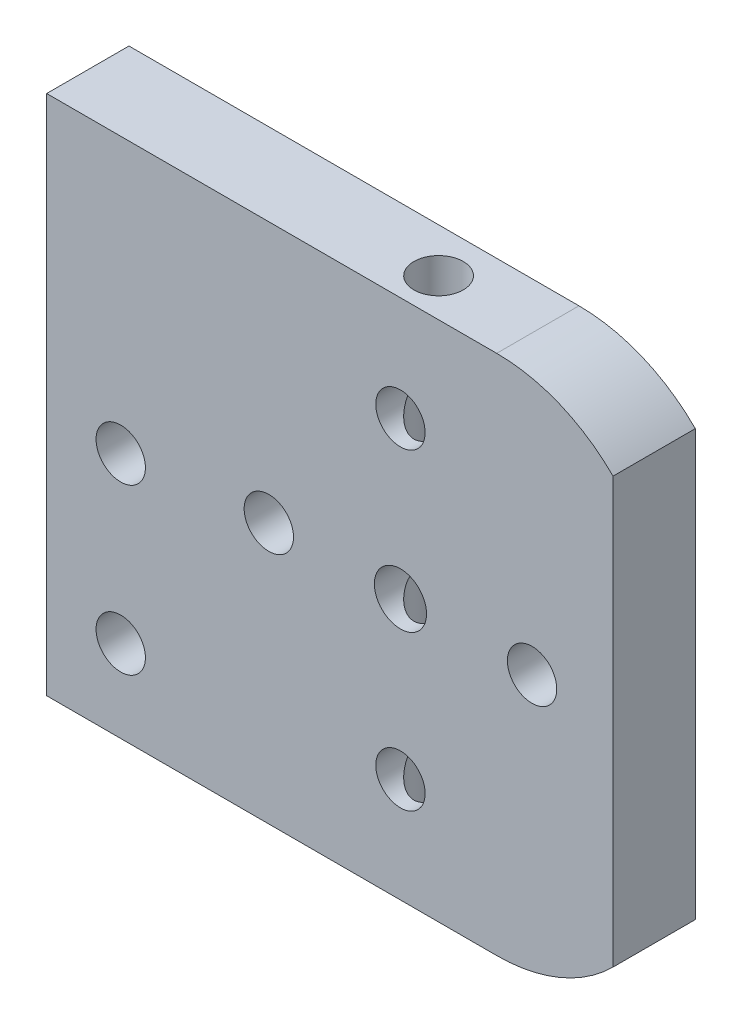
SolidWorks part; units mm, degrees
ref_plane "Alzado" through (0, 0, 0) normal (0, 0, 1) x (1, 0, 0)
ref_plane "Planta" through (0, 0, 0) normal (0, 1, 0) x (1, 0, 0)
ref_plane "Vista lateral" through (0, 0, 0) normal (1, 0, 0) x (0, 0, -1)
sketch "Croquis1" plane through (0, 0, 0) normal (0, 0, 1) x (1, 0, 0)
  line L1 (-13.6328, 23.9366) -> (-13.6328, 2.9366)
  line L2 (-13.6328, 2.9366) -> (-13.6328, -7.7634)
  line L5 (-13.6328, 23.9366) -> (13.7172, 23.9366)
  line L10 (-13.6328, -7.7634) -> (13.7172, -7.7634)
  line L12 (20.7883, 21.0077) -> (20.7883, -4.8344)
  circle A0 centre (7.8672, 8.0866) radius 1.585
  circle A1 centre (-0.1328, 8.0866) radius 1.5
  circle A2 centre (7.8672, -1.4134) radius 1.5
  circle A3 centre (15.8672, 8.0866) radius 1.5
  circle A4 centre (7.8672, 17.5866) radius 1.5
  circle A10 centre (-9.1328, 7.2366) radius 1.5
  circle A11 centre (-9.1328, -2.7634) radius 1.5
  arc A12 (13.7172, -7.7634) -> (20.7883, -4.8344) centre (13.7172, 2.2366) ccw
  arc A13 (20.7883, 21.0077) -> (13.7172, 23.9366) centre (13.7172, 13.9366) ccw
extrude "Saliente-Extruir1" add sketch "Croquis1" along normal blind 5
sketch "Croquis2" plane through (0, 23.9366, 0) normal (0, 1, 0) x (1, 0, 0)
  circle A0 centre (7.8672, -2.6821) radius 1.5
extrude "Cortar-Extruir1" cut sketch "Croquis2" against normal blind 35
